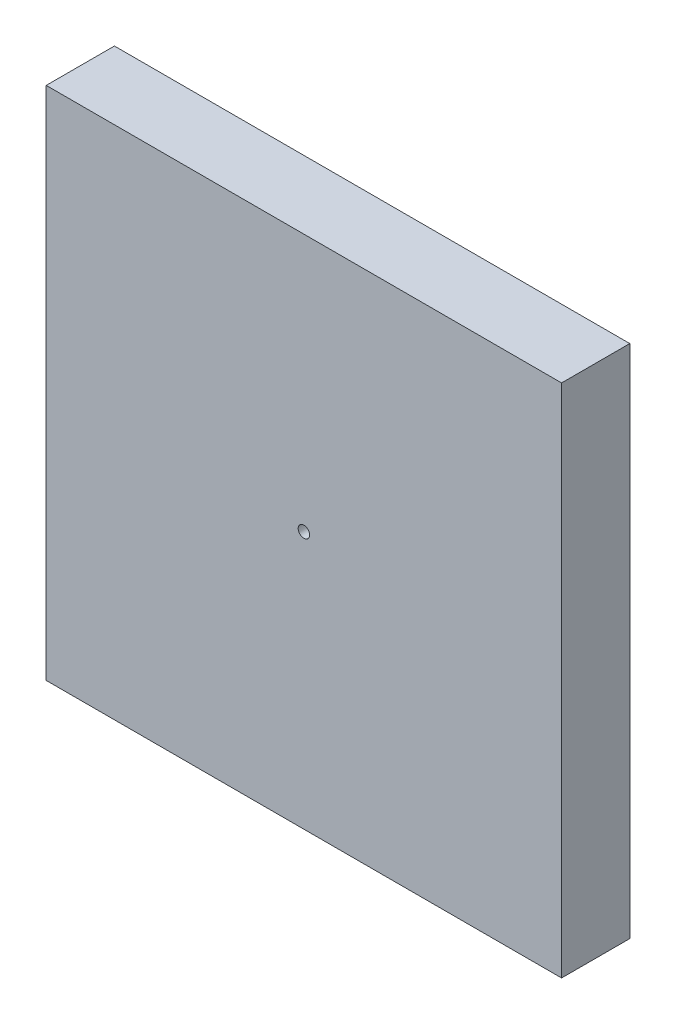
SolidWorks part; units mm, degrees
material "Acrylic (Medium-high impact)"
ref_plane "Front Plane" through (0, 0, 0) normal (0, 0, 1) x (1, 0, 0)
ref_plane "Top Plane" through (0, 0, 0) normal (0, 1, 0) x (1, 0, 0)
ref_plane "Right Plane" through (0, 0, 0) normal (1, 0, 0) x (0, 0, -1)
sketch "Sketch1" plane through (0, 0, 0) normal (0, 0, 1) x (1, 0, 0)
  line L0 (45, -40) -> (135, -40)
  line L1 (135, -40) -> (135, 50)
  line L2 (135, 50) -> (45, 50)
  line L3 (45, 50) -> (45, -40)
  circle A0 centre (90, 5) radius 1
  dimension "D3" = 2
  dimension "D1" = 90
  dimension "D2" = 90
  dimension "D4" = 45
  dimension "D5" = 45
extrude "Boss-Extrude1" add sketch "Sketch1" along normal blind 11.91
